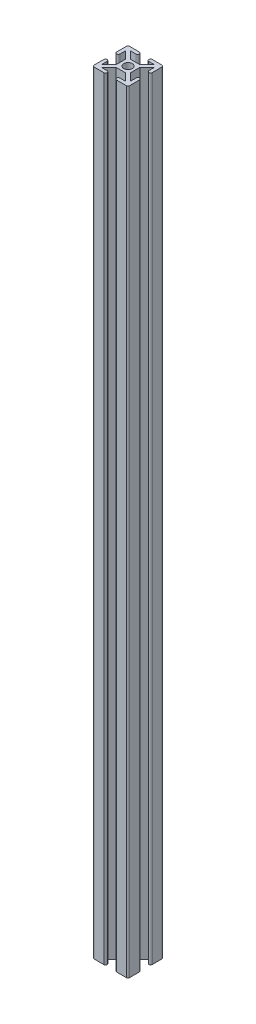
SolidWorks part; units mm, degrees
ref_plane "Alzado" through (0, 0, 0) normal (0, 0, 1) x (1, 0, 0)
ref_plane "Planta" through (0, 0, 0) normal (0, 1, 0) x (1, 0, 0)
ref_plane "Vista lateral" through (0, 0, 0) normal (1, 0, 0) x (0, 0, -1)
sketch "Croquis1" plane through (0, 0, 0) normal (0, 1, 0) x (1, 0, 0)
  line L0 (37.8487, 11.7329) -> (37.8487, 13.1579) construction
  line L1 (56.9015, -4.4171) -> (61.6265, -4.4171)
  line L2 (36.4237, 21.3079) -> (36.4237, 13.1579)
  line L3 (37.8487, 22.7329) -> (45.9987, 22.7329)
  line L4 (56.8487, 22.7329) -> (64.9987, 22.7329)
  line L5 (41.3265, -4.4171) -> (46.0515, -4.4171)
  line L6 (45.4237, 11.7329) -> (45.4237, 3.7329)
  line L7 (36.4765, 2.3079) -> (36.4765, -5.8421)
  line L8 (37.8751, -7.2407) -> (46.0515, -7.2671)
  line L9 (66.4237, 21.3079) -> (66.4237, 13.2616)
  line L10 (39.2737, 17.8829) -> (39.2737, 13.1579)
  line L11 (66.4237, 2.4116) -> (66.4237, -5.8421)
  line L12 (47.4237, 21.3079) -> (45.9987, 21.3079) construction
  line L13 (56.9015, -7.2671) -> (64.9987, -7.2671)
  line L14 (41.2737, 19.8829) -> (45.9987, 19.8829)
  line L15 (39.2737, 2.3079) -> (39.2737, -2.4171)
  line L16 (55.4237, 21.3079) -> (56.8487, 21.3079) construction
  line L17 (56.8487, 19.8829) -> (61.5737, 19.8829)
  line L18 (64.9987, 11.8366) -> (64.9987, 13.2616) construction
  line L19 (47.4237, 13.7329) -> (41.2737, 19.8829)
  line L20 (63.5737, 17.8829) -> (63.5737, 13.2616)
  line L21 (64.9987, 3.8366) -> (64.9987, 2.4116) construction
  line L22 (45.4237, 11.7329) -> (39.2737, 17.8829)
  line L23 (63.5737, 2.4116) -> (63.5737, -2.4171)
  line L24 (55.4765, -5.8421) -> (56.9015, -5.8421) construction
  line L25 (45.4237, 3.7329) -> (39.2737, -2.4171)
  line L26 (47.4237, 13.7329) -> (55.4237, 13.7329)
  line L27 (55.4237, 13.7329) -> (61.5737, 19.8829)
  line L28 (37.8751, 3.7329) -> (37.8751, 2.3079) construction
  line L29 (41.3265, -4.4171) -> (47.4765, 1.7329)
  line L30 (47.4765, 1.7329) -> (55.4765, 1.7329)
  line L31 (55.4765, 1.7329) -> (61.6265, -4.4171)
  line L32 (47.4765, -5.8421) -> (46.0515, -5.8421) construction
  line L33 (57.4237, 3.7329) -> (63.5737, -2.4171)
  line L34 (57.4237, 11.7329) -> (63.5737, 17.8829)
  line L35 (57.4237, 11.7329) -> (57.4237, 3.7329)
  circle A0 centre (51.4765, 7.7329) radius 3.645
  arc A1 (36.4237, 13.1579) -> (39.2737, 13.1579) centre (37.8487, 13.1579) ccw
  arc A2 (45.9987, 19.8829) -> (45.9987, 22.7329) centre (45.9987, 21.3079) ccw
  arc A3 (56.8487, 22.7329) -> (56.8487, 19.8829) centre (56.8487, 21.3079) ccw
  arc A4 (63.5737, 13.2616) -> (66.4237, 13.2616) centre (64.9987, 13.2616) ccw
  arc A5 (66.4237, 2.4116) -> (63.5737, 2.4116) centre (64.9987, 2.4116) ccw
  arc A6 (56.9015, -4.4171) -> (56.9015, -7.2671) centre (56.9015, -5.8421) ccw
  arc A7 (39.2737, 2.3079) -> (36.4765, 2.3079) centre (37.8751, 2.3079) ccw
  arc A8 (46.0515, -7.2671) -> (46.0515, -4.4171) centre (46.0515, -5.8421) ccw
  arc A9 (36.4765, -5.8421) -> (37.8751, -7.2407) centre (37.8751, -5.8421) ccw
  arc A10 (64.9987, -7.2671) -> (66.4237, -5.8421) centre (64.9987, -5.8421) ccw
  arc A11 (66.4237, 21.3079) -> (64.9987, 22.7329) centre (64.9987, 21.3079) ccw
  arc A12 (37.8487, 22.7329) -> (36.4237, 21.3079) centre (37.8487, 21.3079) ccw
  dimension "D1" = 1.425
  dimension "D2" = 1.425
  dimension "D3" = 1.425
  dimension "D4" = 1.425
  dimension "D5" = 1.425
  dimension "D6" = 1.425
  dimension "D7" = 1.425
  dimension "D8" = 1.425
extrude "Saliente-Extruir1" add sketch "Croquis1" along normal blind 650
sketch "Croquis2" plane through (0, 0, -1.7329) normal (0, 0, 1) x (1, 0, 0)
  line L0 (47.4765, 0) -> (55.4765, 0) construction
  line L1 (56.9015, 0) -> (64.9987, 0) construction
  circle A0 centre (51.4765, 18.84) radius 4
  point P4 (51.4765, 0)
  dimension "D3" = 8
  dimension "D1" = 0
  dimension "D2" = 18.84
extrude "Cortar-Extruir1" cut sketch "Croquis2" against normal blind 10
sketch "Croquis3" plane through (0, 0, -1.7329) normal (0, 0, 1) x (1, 0, 0)
  circle A0 centre (51.4765, 18.84) radius 4
  circle A1 centre (51.4765, 75.14) radius 4
  circle A2 centre (51.4765, 198.84) radius 4
  circle A3 centre (51.4765, 255.14) radius 4
  dimension "D2" = 8
  dimension "D3" = 8
  dimension "D6" = 8
  dimension "D1" = 56.3
  dimension "D4" = 180
  dimension "D5" = 180
extrude "Cortar-Extruir2" cut sketch "Croquis3" against normal blind 50
sketch "Sketch1" plane through (45.4237, 0, 0) normal (-1, 0, 0) x (0, 0, 1)
  circle A0 centre (-7.7858, 635) radius 4
  dimension "D1" = 8
extrude "Cut-Extrude1" cut sketch "Sketch1" against normal blind 12
